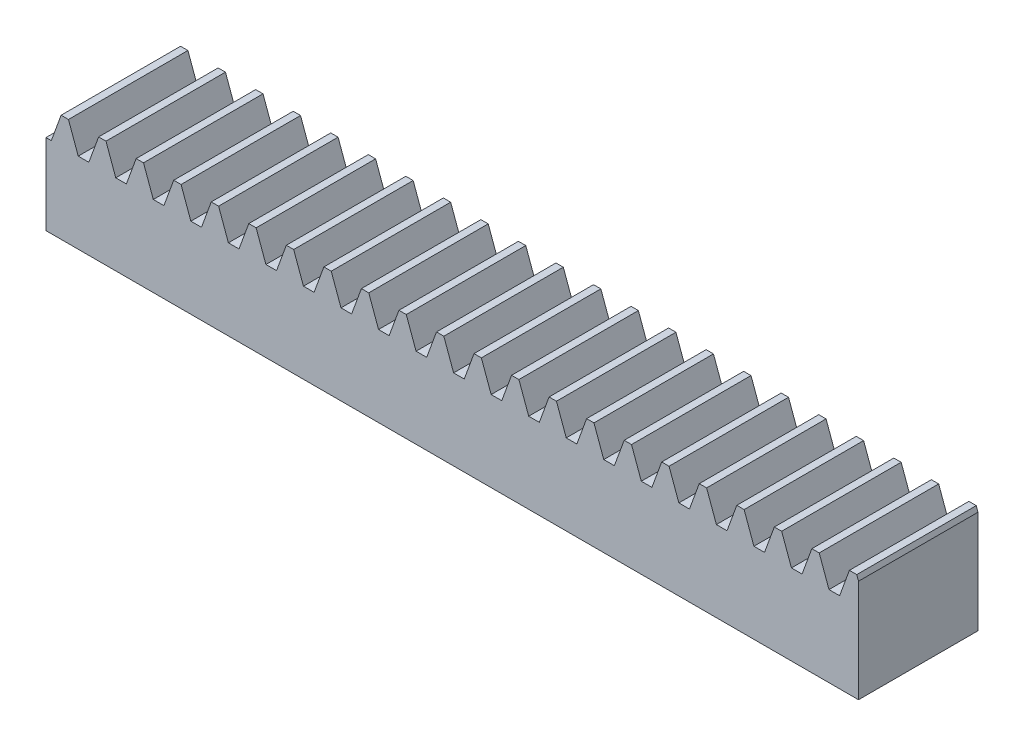
SolidWorks part; units mm, degrees
extrude "Blank" add sketch "BlankSke" against normal blind 5
sketch "BlankSke" plane through (0, 0, 0) normal (0, 0, 1) x (1, 0, 0)
  line L1 (0, 0) -> (34, 0)
  line L2 (0, 0) -> (0, 4.5)
  line L3 (0, 4.5) -> (34, 4.5)
  line L4 (34, 0) -> (34, 4.5)
  dimension "Length" = 34
  dimension "Blank_height" = 4.5
ref_plane "Plane1" through (0, 0, 0) normal (0, 0, 1) x (1, 0, 0)
ref_plane "Plane2" through (0, 0, 0) normal (0, 1, 0) x (1, 0, 0)
ref_plane "Plane3" through (0, 0, 0) normal (1, 0, 0) x (0, 0, -1)
sketch "HoldingSke" plane through (0, 0, 0) normal (0, 1, 0) x (1, 0, 0)
  line L0 (0, 0) -> (0.2783, 1.9805)
  line L1 (-15, 0) -> (100, 0) construction
  line L2 (0, 0) -> (-2.1039, 2.3779)
  line L3 (0, 0) -> (-11.863, 4.5341)
  line L4 (0, 0) -> (7.9495, 3.3743)
  line L5 (0, 0) -> (-23.7986, -8.8762)
  line L6 (0, 0) -> (-10.5278, -7.1032)
  line L9 (-71.009, 38.7566) -> (-39.0594, 50.3853)
  line L10 (-76.2, 2.8779) -> (-72.2, 2.8779)
  line L11 (0, 0) -> (-5, 0)
  line L12 (-76.2, 101.6) -> (-76.181, 101.6)
  line L13 (24.9733, 27.94) -> (52.9518, 28.4284)
  line L14 (24.9733, 27.94) -> (24.9743, 27.94)
  line L15 (24.9733, 27.94) -> (100.4006, 29.5858)
  circle A0 centre (0, 0) radius 19.05
  circle A1 centre (0, 0) radius 2
  circle A2 centre (0, 0) radius 12.7
  dimension "MPH" = 4
  dimension "Diameter" = 38.1
  dimension "Num_teeth" = 23
  dimension "Pitch" = 2
  dimension "Show_teeth" = 998
  dimension "Thickness" = 12.7
  dimension "Ap" = 20
  dimension "Pitch_height" = 4
  dimension "Width" = 5
  dimension "Backlash" = 0.019
  dimension "Addendum_fac" = 1
  dimension "Dedendum_fac" = 1.25
  dimension "Clearance_fac" = 0.25
  dimension "Dedendum_add" = 0.001
  dimension "Length" = 34
  dimension "Module" = 0.5
sketch "TooCutSkeIll" plane through (0, 0, 0) normal (0, 0, 1) x (1, 0, 0)
  line L0 (-0.6269, 4.4868) -> (-0.2524, 3.4579)
  line L1 (-0.134, 3.375) -> (0.134, 3.375)
  line L2 (0.2524, 3.4579) -> (0.6269, 4.4868)
  line L3 (34, 4.5) -> (0, 4.5) construction
  line L4 (0, 0) -> (0, 64.897) construction
  line L5 (-13.208, 4) -> (12.954, 4) construction
  line L6 (0, 0) -> (34, 0) construction
  line L7 (0.4497, 4) -> (0.4497, 48.7463) construction
  line L8 (-0.4497, 4) -> (-0.4497, 48.7463) construction
  line L9 (0.6457, 4.5) -> (0.6457, 4.5254)
  line L10 (-0.6457, 4.5) -> (-0.6457, 4.5254)
  line L11 (-0.6457, 4.5254) -> (0.6457, 4.5254)
  arc A0 (0.134, 3.375) -> (0.2524, 3.4579) centre (0.134, 3.501) ccw
  arc A1 (-0.2524, 3.4579) -> (-0.134, 3.375) centre (-0.134, 3.501) ccw
  arc A2 (0.6457, 4.5) -> (0.6269, 4.4868) centre (0.6457, 4.48) ccw
  arc A3 (-0.6269, 4.4868) -> (-0.6457, 4.5) centre (-0.6457, 4.48) ccw
  dimension "Pitch_height" = 4
  dimension "Addendum_plus" = 0.5254
  dimension "Pressure_angle" = 20
  dimension "Gap_width" = 0.8994
  dimension "Dedendum" = 0.625
extrude "ToothCutIll" [suppressed] cut sketch "TooCutSkeIll" against normal through all
sketch "TooCutSkeSim" plane through (0, 0, 0) normal (0, 0, 1) x (1, 0, 0)
  line L0 (0.2222, 3.375) -> (-0.2222, 3.375)
  line L1 (0.6409, 4.5254) -> (0.2222, 3.375)
  line L2 (0, 17.4625) -> (0, 53.467) construction
  line L3 (0.6409, 4.5254) -> (-0.6409, 4.5254)
  line L6 (-0.6409, 4.5254) -> (-0.2222, 3.375)
  line L9 (-0.4497, 4) -> (0.4497, 4) construction
  line L10 (0, 0) -> (34, 0) construction
  line L11 (0.4497, 4) -> (0.4497, 53.467) construction
  line L12 (-0.4497, 4) -> (-0.4497, 53.467) construction
  dimension "Pitch_height" = 4
  dimension "Addendum_plus" = 0.5254
  dimension "Pressure_angle" = 20
  dimension "Gap_width" = 0.8994
  dimension "Dedendum" = 0.625
extrude "ToothCutSim" cut sketch "TooCutSkeSim" against normal through all
pattern_linear "TeethCuts" count 22 spacing 1.5708 along (1, 0, 0) of "ToothCutIll", "ToothCutSim"
equation "' \"Module@HoldingSke\" = 6.35"
equation "' \"Num_teeth@HoldingSke\" = 12"
equation "' \"Ap@HoldingSke\" =  20"
equation "' \"Ap@HoldingSke\" = 20"
equation "' \"Width@HoldingSke\" = 0.25 * 25.4"
equation "' \"Show_teeth@HoldingSke\" = 500"
equation "' \"Backlash@HoldingSke\" = 0.009 * 25.4"
equation "' \"Addendum_fac@HoldingSke\" = 1.0"
equation "' \"Dedendum_fac@HoldingSke\" = 1.25"
equation "' \"Dedendum_add@HoldingSke\" = 0.00005 * 25.4"
equation "' \"Clearance_fac@HoldingSke\" = 0.25"
equation "' \"Pitch_height@HoldingSke\" = 1 * 25.4"
equation "' \"Length@HoldingSke\" = 4.71 * 25.4"
equation "\"Pitch@HoldingSke\" = 1 / \"Module@HoldingSke\""
equation "\"MPH@HoldingSke\" = \"Dedendum_fac@HoldingSke\" / \"Pitch@HoldingSke\" + 2 * \"Dedendum_add@HoldingSke\" + 0.002 * 25.4"
equation "\"MPH@HoldingSke\" = ((sgn( \"MPH@HoldingSke\" - \"Pitch_height@HoldingSke\")+1)*( \"MPH@HoldingSke\" - \"Pitch_height@HoldingSke\"))/2 + \"Pitch_height@HoldingSke\""
equation "\"Blank_height@BlankSke\" = \"Pitch_height@HoldingSke\" + \"Addendum_fac@HoldingSke\"  / \"Pitch@HoldingSke\" "
equation "\"Length@BlankSke\" =  \"Length@HoldingSke\""
equation "\"Face_width@Blank\" = \"Width@HoldingSke\""
equation "\"Pressure_angle@TooCutSkeIll\" = \"Ap@HoldingSke\""
equation "\"Addendum_plus@TooCutSkeIll\" =  \"Addendum_fac@HoldingSke\"  / \"Pitch@HoldingSke\" + 0.001 *25.4"
equation "\"Dedendum@TooCutSkeIll\" = \"Dedendum_fac@HoldingSke\"  / \"Pitch@HoldingSke\""
equation "\"Pitch_height@TooCutSkeIll\" =  \"MPH@HoldingSke\""
equation "\"Gap_width@TooCutSkeIll\" = 3.14159265 / 2 / \"Pitch@HoldingSke\" + 6 * \"Backlash@HoldingSke\""
equation "\"Pressure_angle@TooCutSkeSim\" = \"Ap@HoldingSke\""
equation "\"Addendum_plus@TooCutSkeSim\" =  \"Addendum_fac@HoldingSke\"  / \"Pitch@HoldingSke\" + 0.001 * 25.4"
equation "\"Dedendum@TooCutSkeSim\" = \"Dedendum_fac@HoldingSke\"  / \"Pitch@HoldingSke\""
equation "\"Pitch_height@TooCutSkeSim\" =  \"MPH@HoldingSke\""
equation "\"Gap_width@TooCutSkeSim\" = 3.14159265 / 2 / \"Pitch@HoldingSke\" + 6 * \"Backlash@HoldingSke\""
equation "\"Root_fillet@TooCutSkeIll\" = \"Clearance_fac@HoldingSke\" / \"Pitch@HoldingSke\" + \"Dedendum_add@HoldingSke\""
equation "\"Break_rad@TooCutSkeIll\" = 0.02 / \"Pitch@HoldingSke\" * 2"
equation "\"Linear_pitch@TeethCuts\" = 3.14159265 / \"Pitch@HoldingSke\""
equation "\"Num_teeth@HoldingSke\" = int( ( \"Length@HoldingSke\" + 0 ) / (3.14159265 / \"Pitch@HoldingSke\")) + 0.9999  + 1"
equation " \"Num_teeth@TeethCuts\" = int( \"Show_teeth@HoldingSke\" ) + 1"
equation " \"Num_teeth@TeethCuts\" = ((sgn( \"Num_teeth@TeethCuts\" - \"Num_teeth@HoldingSke\" )-1)*( \"Num_teeth@TeethCuts\" - \"Num_teeth@HoldingSke\" ))/-2+ \"Num_teeth@HoldingSke\""
equation " \"Num_teeth@TeethCuts\" = ((sgn( \"Num_teeth@TeethCuts\" - 2.0)+1)*( \"Num_teeth@TeethCuts\" - 2.0))/2 +2.0"
